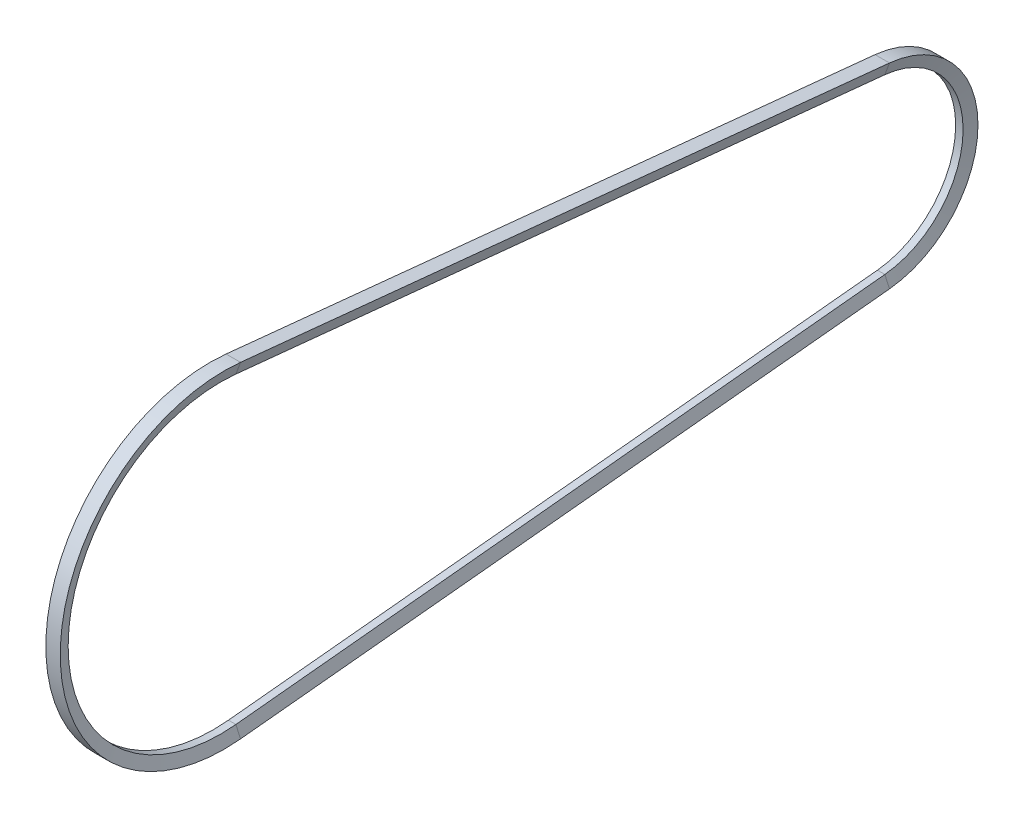
SolidWorks part; units mm, degrees
ref_plane "前视基准面" through (0, 0, 0) normal (0, 0, 1) x (1, 0, 0)
ref_plane "上视基准面" through (0, 0, 0) normal (0, 1, 0) x (1, 0, 0)
ref_plane "右视基准面" through (0, 0, 0) normal (1, 0, 0) x (0, 0, -1)
sketch "草图1" plane through (0, 0, 0) normal (1, 0, 0) x (0, 0, -1)
  line L0 (12.5, 124.3734) -> (507.5, 74.6241)
  line L1 (12.5, -124.3734) -> (507.5, -74.6241)
  line L2 (0, 0) -> (500, 0) construction
  arc A0 (12.5, 124.3734) -> (12.5, -124.3734) centre (0, 0) ccw
  arc A1 (507.5, -74.6241) -> (507.5, 74.6241) centre (500, 0) ccw
  dimension "D1" = 125
  dimension "D2" = 75
  dimension "D3" = 500
sketch "草图2" plane through (0, 0, 0) normal (0, 0, 1) x (1, 0, 0)
  line L0 (-5.5, 125) -> (5.5, 125)
  line L1 (5.5, 125) -> (2.8401, 116.3)
  line L2 (2.8401, 116.3) -> (-2.8401, 116.3)
  line L3 (-2.8401, 116.3) -> (-5.5, 125)
  line L4 (0, 116.3) -> (0, 125) construction
  line L5 (0, -125) -> (0, 125) construction
  dimension "D1" = 11
  dimension "D2" = 8.7
  dimension "D3" = 34
sweep "扫描1" add profiles "草图2" path "草图1"
equation "\"D3@草图1\" = \"D1@距离1@辐板轮_孔板轮.Assembly\""
equation "\"D1@草图2\" = \"bd@草图1@大带轮_孔板轮.Part\" "
equation "\"D2@草图2\" = \"hf@草图1@大带轮_孔板轮.Part\" "
equation "\"D3@草图2\" = \"槽轮角@草图1@大带轮_孔板轮.Part\" "
equation " \"D2@草图1\" = \"dd@草图1@小带轮_辐板轮.Part\"/2"
equation "\"D1@草图1\" = \"dd@草图1@大带轮_孔板轮.Part\" /2"
